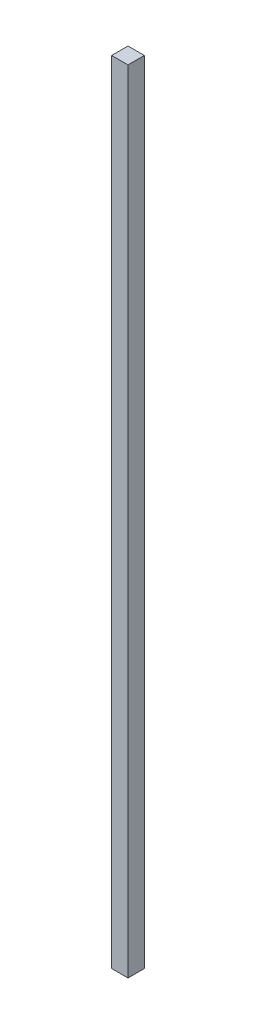
SolidWorks part; units mm, degrees
material "Alloy Steel"
ref_plane "Front Plane" through (0, 0, 0) normal (1, 0, 0) x (0, 1, 0)
ref_plane "Top Plane" through (0, 0, 0) normal (0, 0, 1) x (0, 1, 0)
ref_plane "Right Plane" through (0, 0, 0) normal (0, 1, 0) x (-1, 0, 0)
sketch "Sketch2" plane through (0, 0, 0) normal (1, 0, 0) x (0, 1, 0)
  line L0 (0, 0) -> (10000, 0)
  dimension "D1" = 10000
other "Building 3IN(1)"
ref_plane "Plane1" through (0, 0, 0) normal (0, 1, 0) x (0, 0, 1)
sketch "Sketch21" plane through (0, 0, 0) normal (0, 1, 0) x (0, 0, 1)
  line L1 (0, 0) -> (207, 0)
  line L2 (0, 0) -> (0, 207)
  line L3 (0, 207) -> (207, 207)
  line L4 (207, 0) -> (207, 207)
  point P3 (0, 0)
  dimension "D1" = 207
